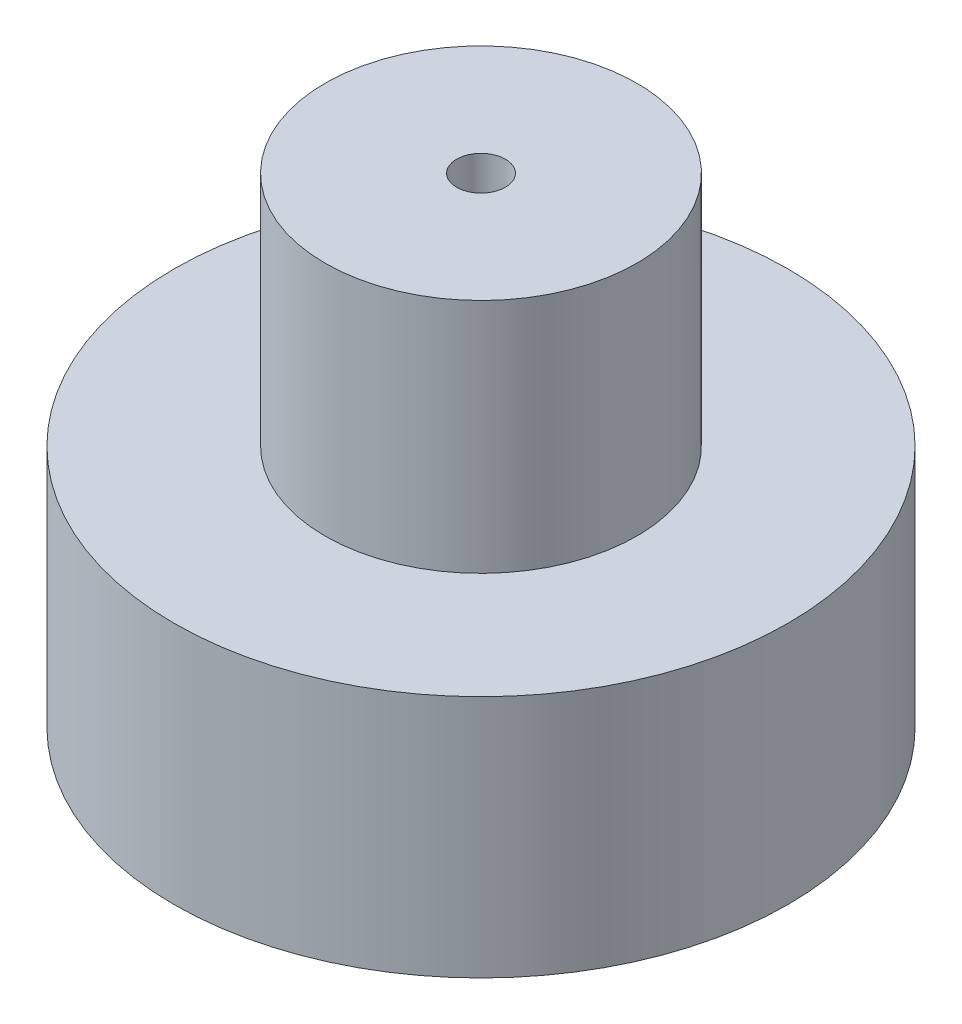
SolidWorks part; units mm, degrees
ref_plane "Plan de face" through (0, 0, 0) normal (0, 0, 1) x (1, 0, 0)
ref_plane "Plan de dessus" through (0, 0, 0) normal (0, 1, 0) x (1, 0, 0)
ref_plane "Plan de droite" through (0, 0, 0) normal (1, 0, 0) x (0, 0, -1)
sketch "Esquisse1" plane through (0, 0, 0) normal (0, 1, 0) x (1, 0, 0)
  circle A0 centre (0, 0) radius 12.6
  dimension "D1" = 25.2
extrude "Boss.-Extru.1" add sketch "Esquisse1" along normal blind 10 contours A0
sketch "Esquisse2" plane through (0, 10, 0) normal (0, 1, 0) x (1, 0, 0)
  circle A0 centre (0, 0) radius 6.4
  dimension "D1" = 12.8
extrude "Boss.-Extru.2" add sketch "Esquisse2" along normal blind 9.7
hole_wizard "Dégagement M1.61" positions "Esquisse9" profile "Esquisse11" hole size "M1.6" standard "Ansi Metric" end condition through all
sketch "Esquisse9" plane through (0, 19.7, 0) normal (0, 1, 0) x (1, 0, 0)
  point P0 (0, 0)
sketch "Esquisse11" plane through (0, 19.7, 0) normal (1, 0, 0) x (0, 0, 1)
  line L0 (0, 0) -> (0, 19.7)
  line L1 (0, 19.7) -> (1, 19.7)
  line L2 (1, 19.7) -> (1, 0)
  line L5 (1, 0) -> (0, 0)
  line L11 (0, -6.35) -> (0, 107.95) construction
  dimension "Diamètre du perçage jusqu'au prochain" = 2
  dimension "Profondeur du perçage jusqu'au prochain" = 19.7
